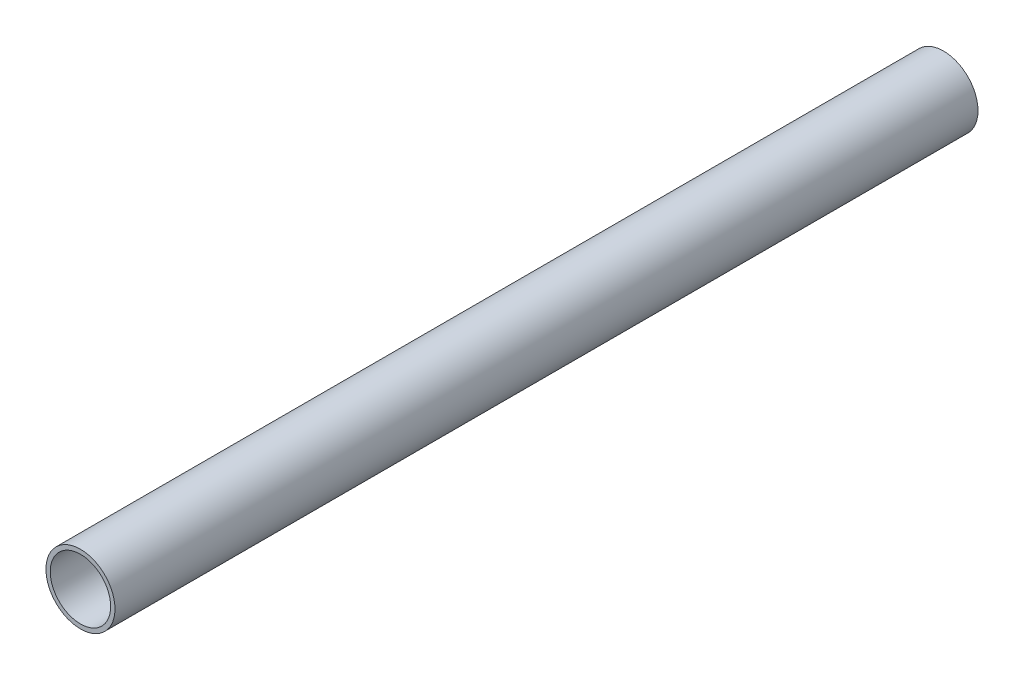
SolidWorks part; units mm, degrees
ref_plane "Front Plane" through (0, 0, 0) normal (0, 0, 1) x (1, 0, 0)
ref_plane "Top Plane" through (0, 0, 0) normal (0, 1, 0) x (1, 0, 0)
ref_plane "Right Plane" through (0, 0, 0) normal (1, 0, 0) x (0, 0, -1)
sketch "Sketch1" plane through (0, 0, 0) normal (0, 0, 1) x (1, 0, 0)
  circle A0 centre (0, 0) radius 7
  circle A1 centre (0, 0) radius 8
  dimension "D1" = 14
  dimension "D2" = 16
extrude "Boss-Extrude1" add sketch "Sketch1" along normal mid plane 200
